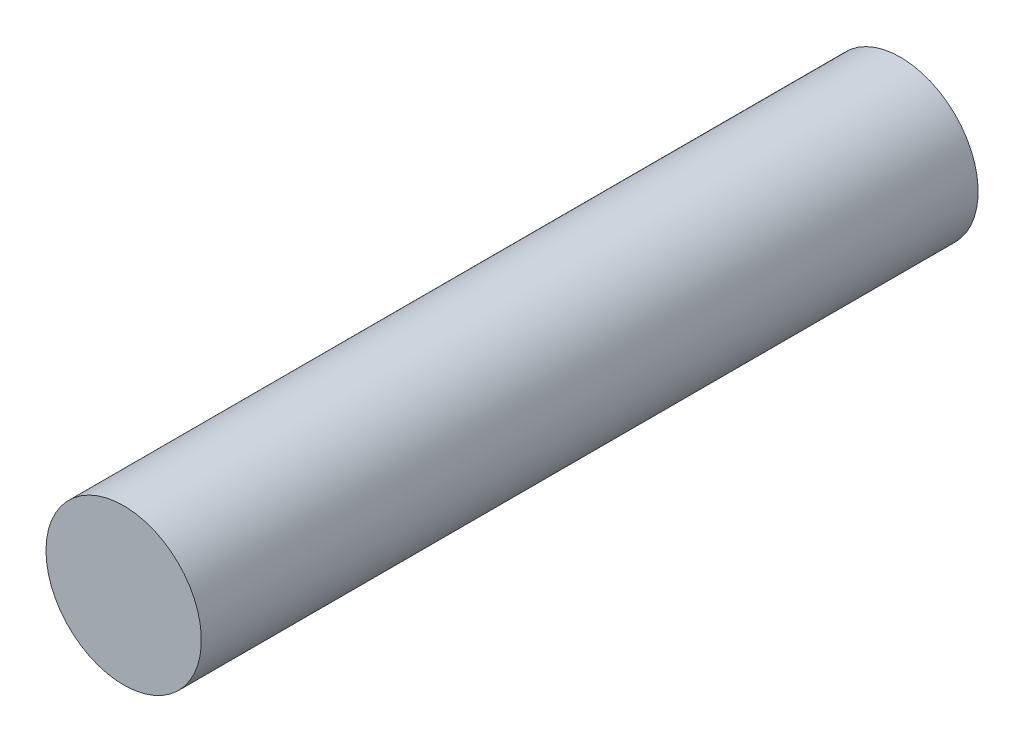
SolidWorks part; units mm, degrees
ref_plane "Front Plane" through (0, 0, 0) normal (0, 0, 1) x (1, 0, 0)
ref_plane "Top Plane" through (0, 0, 0) normal (0, 1, 0) x (1, 0, 0)
ref_plane "Right Plane" through (0, 0, 0) normal (1, 0, 0) x (0, 0, -1)
sketch "Sketch1" plane through (0, 0, 0) normal (0, 0, 1) x (1, 0, 0)
  circle A0 centre (0, 0) radius 7.9375
  dimension "D1" = 15.875
extrude "Boss-Extrude1" add sketch "Sketch1" along normal blind 79.375
